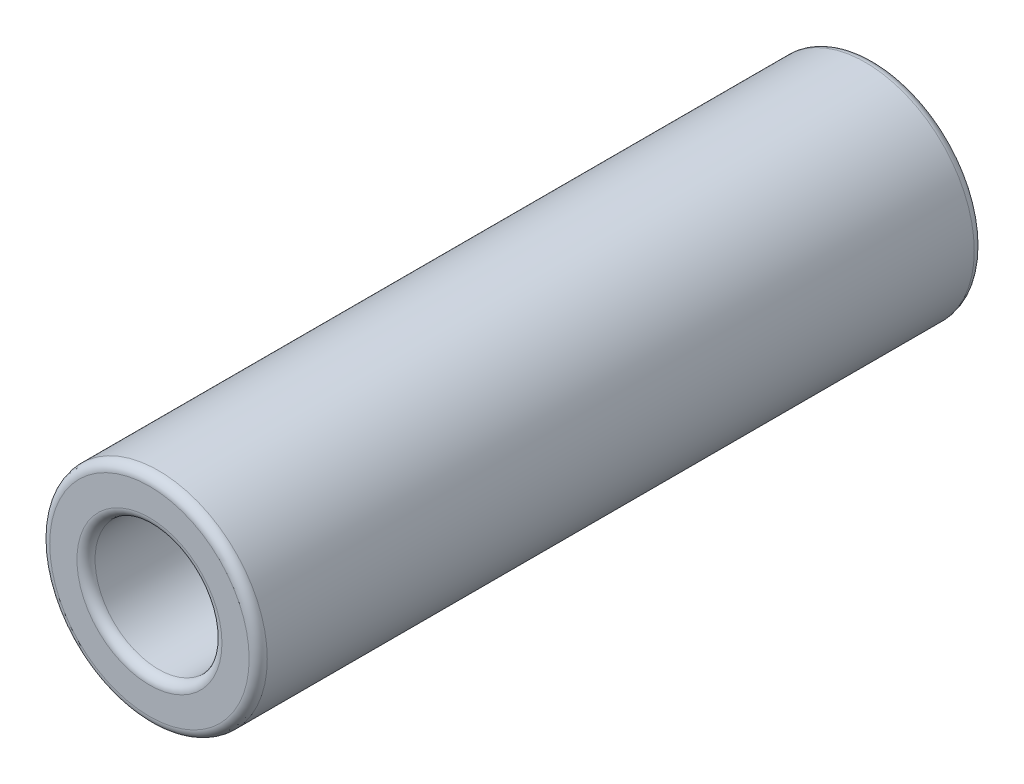
SolidWorks part; units mm, degrees
ref_plane "Płaszczyzna przednia" through (0, 0, 0) normal (0, 0, 1) x (1, 0, 0)
ref_plane "Płaszczyzna górna" through (0, 0, 0) normal (0, 1, 0) x (1, 0, 0)
ref_plane "Płaszczyzna prawa" through (0, 0, 0) normal (1, 0, 0) x (0, 0, -1)
sketch "Szkic1" plane through (0, 0, 0) normal (0, 0, 1) x (1, 0, 0)
  circle A0 centre (0, 0) radius 6
  circle A1 centre (0, 0) radius 3.5
  dimension "D1" = 12
  dimension "D2" = 7
extrude "Dodanie-wyciągnięcie1" add sketch "Szkic1" along normal blind 40
fillet "Zaokrąglenie1" radius 0.5 4 edges at (6, 0, 0) (3.5, 0, 0) (3.5, 0, 40) (6, 0, 40)
